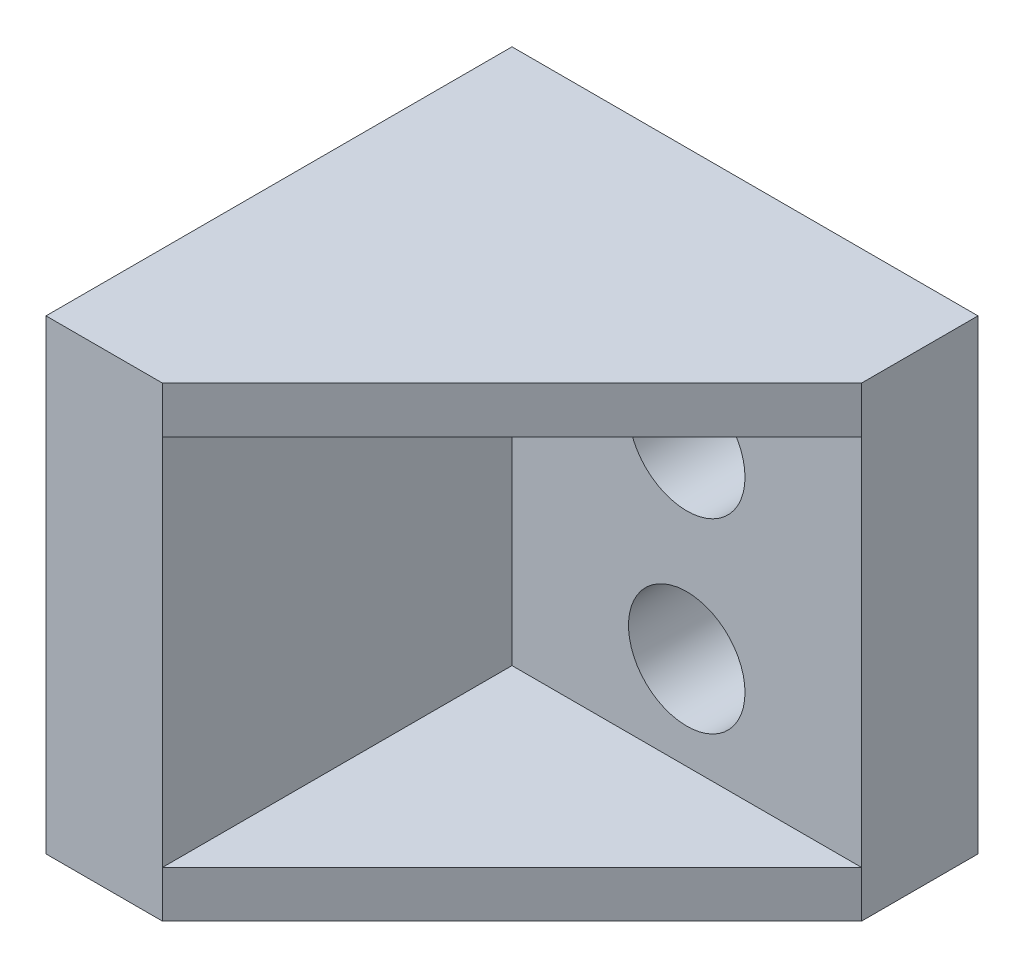
SolidWorks part; units mm, degrees
ref_plane "Front Plane" through (0, 0, 0) normal (0, 0, 1) x (1, 0, 0)
ref_plane "Top Plane" through (0, 0, 0) normal (0, 1, 0) x (1, 0, 0)
ref_plane "Right Plane" through (0, 0, 0) normal (1, 0, 0) x (0, 0, -1)
sketch "Sketch2" plane through (0, 0, 0) normal (0, 1, 0) x (1, 0, 0)
  line L1 (-5, 2.5) -> (5, 2.5)
  line L2 (-5, 2.5) -> (-5, -2.5)
  line L3 (-2.5, 0) -> (5, 0)
  line L4 (5, 2.5) -> (5, 0)
  line L7 (-5, 2.5) -> (0, 2.5)
  line L8 (-5, 2.5) -> (-5, -7.5)
  line L9 (-5, -7.5) -> (-2.5, -7.5)
  line L10 (-2.5, 0) -> (-2.5, -7.5)
  point P0 (0, 0)
  dimension "D1" = 2.5
  dimension "D2" = 2.5
  dimension "D3" = 10
  dimension "D4" = 10
extrude "Boss-Extrude1" add sketch "Sketch2" along normal blind 10 contours L10 L3 L4 L1 L2 L8 L9
sketch "Sketch3" plane through (0, 0, 0) normal (0, 0, 1) x (1, 0, 0)
  line L0 (-2.5, 10) -> (-2.5, 0) construction
  line L1 (-2.5, 10) -> (5, 10) construction
  circle A0 centre (1.25, 7) radius 1.25
  dimension "D1" = 2.5
  dimension "D2" = 3.75
  dimension "D3" = 3
extrude "Cut-Extrude1" cut sketch "Sketch3" against normal blind 10
ref_plane "Plane1" through (0, 5, 0) normal (0, -1, 0) x (-1, 0, 0)
mirror "Mirror1" about plane through (0, 5, 0) normal (0, -1, 0) of "Cut-Extrude1"
sketch "Sketch4" plane through (0, 10, 0) normal (0, 1, 0) x (1, 0, 0)
  line L0 (-2.5, -7.5) -> (5, 0)
  line L1 (5, 0) -> (-2.5, 0)
  line L2 (-2.5, 0) -> (-2.5, -7.5)
extrude "Boss-Extrude2" add sketch "Sketch4" against normal blind 1
mirror "Mirror2" about plane through (0, 5, 0) normal (0, -1, 0) of "Boss-Extrude2"
